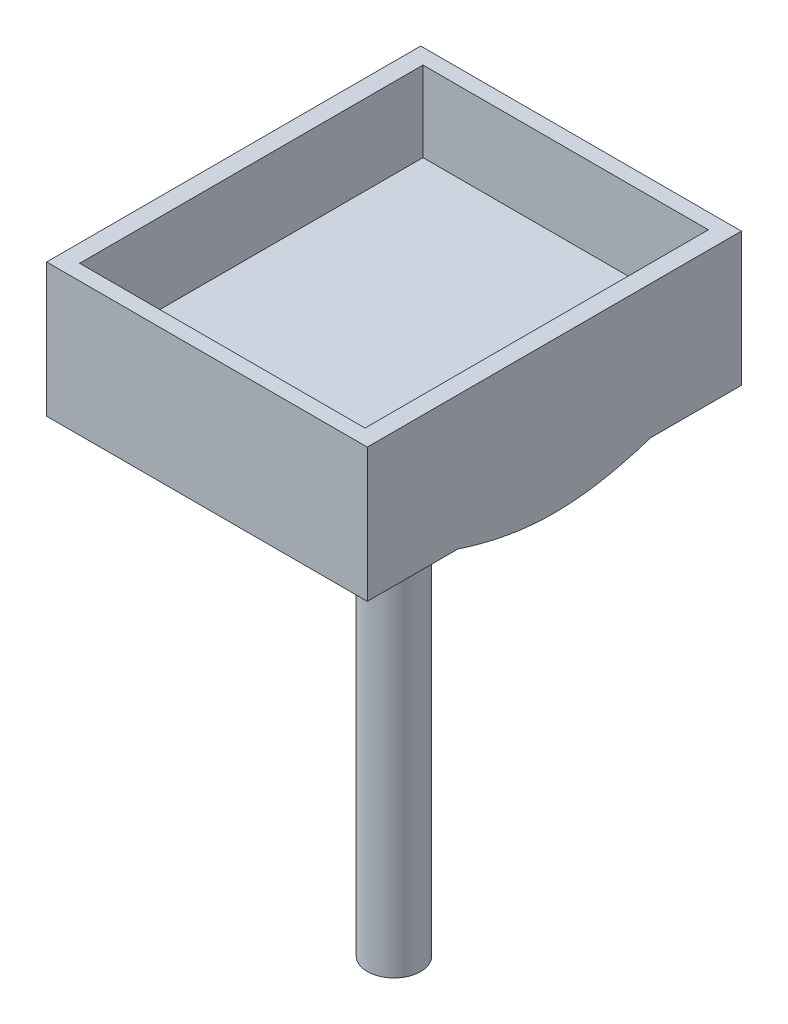
SolidWorks part; units mm, degrees
ref_plane "Front Plane" through (0, 0, 0) normal (0, 0, 1) x (1, 0, 0)
ref_plane "Top Plane" through (0, 0, 0) normal (0, 1, 0) x (1, 0, 0)
ref_plane "Right Plane" through (0, 0, 0) normal (1, 0, 0) x (0, 0, -1)
sketch "Sketch1" plane through (0, 0, 0) normal (0, 1, 0) x (1, 0, 0)
  circle A0 centre (0, 0) radius 5
  dimension "D1" = 10
extrude "Boss-Extrude1" add sketch "Sketch1" along normal blind 90
sketch "Sketch2" plane through (0, 0, 0) normal (0, 1, 0) x (1, 0, 0)
  line L1 (-30, 35) -> (30, 35)
  line L2 (-30, 35) -> (-30, -35)
  line L3 (-30, -35) -> (30, -35)
  line L4 (30, 35) -> (30, -35)
  line L5 (-30, 35) -> (30, -35) construction
  line L6 (-30, -35) -> (30, 35) construction
  point P0 (0, 0)
  dimension "D1" = 60
  dimension "D2" = 70
extrude "Boss-Extrude2" add sketch "Sketch2" along normal blind 25 from surface at 90 starting at face at (0, 90, 5)
sketch "Sketch4" plane through (0, 0, 0) normal (1, 0, 0) x (0, 0, -1)
  line L0 (-35, 90) -> (-5, 70.95)
  line L1 (-5, 90) -> (-5, 0) construction
  line L2 (-5, 70.95) -> (-5, 90)
  line L3 (-5, 90) -> (-35, 90)
  line L4 (0, 90) -> (0, 0) construction
  line L5 (-5, 90) -> (5, 90) construction
  point P12 (0, 0)
  point P13 (-35, 80)
  dimension "D1" = 19.05
revolve "Revolve1" add sketch "Sketch4" angle 360 about L4
sketch "Sketch5" plane through (0, 0, 0) normal (0, 1, 0) x (1, 0, 0)
  line L1 (-30, 35) -> (30, 35)
  line L2 (-30, 35) -> (-30, -35)
  line L3 (-30, -35) -> (30, -35)
  line L4 (30, 35) -> (30, -35)
  line L5 (-38.494, 39.6539) -> (38.494, 39.6539)
  line L6 (-38.494, 39.6539) -> (-38.494, -39.6539)
  line L7 (-38.494, -39.6539) -> (38.494, -39.6539)
  line L8 (38.494, 39.6539) -> (38.494, -39.6539)
  line L9 (-38.494, 39.6539) -> (38.494, -39.6539) construction
  line L10 (-38.494, -39.6539) -> (38.494, 39.6539) construction
  point P6 (0, 0)
extrude "Cut-Extrude1" cut sketch "Sketch5" along normal through all both and the other way through all
sketch "Sketch6" plane through (0, 0, 0) normal (0, 1, 0) x (1, 0, 0)
  line L1 (-26.7, 32.125) -> (26.7, 32.125)
  line L2 (-26.7, 32.125) -> (-26.7, -32.125)
  line L3 (-26.7, -32.125) -> (26.7, -32.125)
  line L4 (26.7, 32.125) -> (26.7, -32.125)
  line L5 (-26.7, 32.125) -> (26.7, -32.125) construction
  line L6 (-26.7, -32.125) -> (26.7, 32.125) construction
  point P0 (0, 0)
  dimension "D1" = 53.4
  dimension "D2" = 64.25
extrude "Cut-Extrude2" cut sketch "Sketch6" against normal blind 15 from surface at 115 starting at face at (0, 115, 0)
